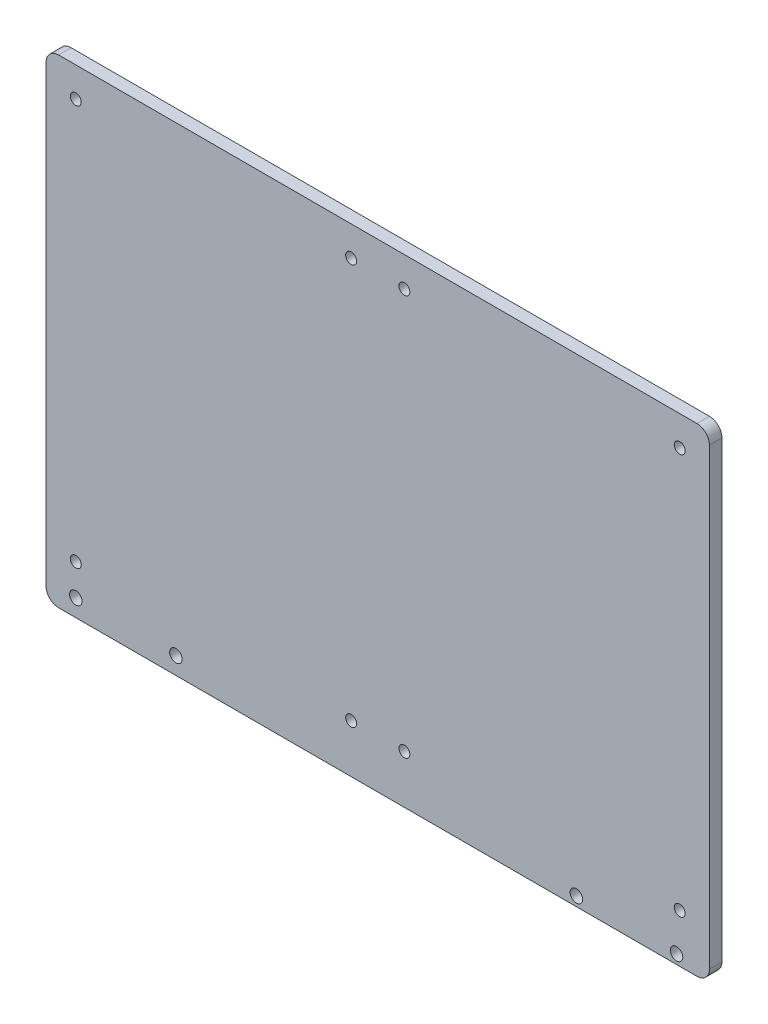
SolidWorks part; units mm, degrees
ref_plane "Front Plane" through (0, 0, 0) normal (0, 0, 1) x (1, 0, 0)
ref_plane "Top Plane" through (0, 0, 0) normal (0, 1, 0) x (1, 0, 0)
ref_plane "Right Plane" through (0, 0, 0) normal (1, 0, 0) x (0, 0, -1)
sketch "Sketch1" plane through (0, 0, 0) normal (0, 0, 1) x (1, 0, 0)
  line L1 (106, -76.5) -> (-106, -76.5)
  line L2 (106, -76.5) -> (106, 76.5)
  line L3 (106, 76.5) -> (-106, 76.5)
  line L4 (-106, -76.5) -> (-106, 76.5)
  line L5 (0, 76.5) -> (0, -76.5) construction
  line L6 (106, 0) -> (-106, 0) construction
  line L7 (-104, 74.5) -> (-1, 74.5) construction
  line L8 (-104, 74.5) -> (-104, -68.5) construction
  line L9 (-104, -68.5) -> (-1, -68.5) construction
  line L10 (-1, 74.5) -> (-1, -68.5) construction
  line L11 (-52.5, -68.5) -> (-52.5, 74.5) construction
  line L12 (-104, 3) -> (-1, 3) construction
  line L13 (1, 74.5) -> (104, 74.5) construction
  line L14 (1, 74.5) -> (1, -68.5) construction
  line L15 (1, -68.5) -> (104, -68.5) construction
  line L16 (104, 74.5) -> (104, -68.5) construction
  line L17 (52.5, -68.5) -> (52.5, 74.5) construction
  line L18 (1, 3) -> (104, 3) construction
  circle A0 centre (-96.5, -61) radius 1.75
  circle A1 centre (-8.5, -61) radius 1.75
  circle A2 centre (8.5, -61) radius 1.75
  circle A3 centre (96.5, -61) radius 1.75
  circle A4 centre (-96.5, 67) radius 1.75
  circle A5 centre (96.5, 67) radius 1.75
  circle A6 centre (8.5, 67) radius 1.75
  circle A7 centre (-8.5, 67) radius 1.75
  circle A8 centre (-96.5, -71) radius 2
  circle A9 centre (95.4803, -73.51) radius 2
  circle A10 centre (-64.5, -71) radius 2
  circle A11 centre (63.4803, -73.51) radius 2
  point P0 (0, 0)
  point P226 (-52.5, 3)
  point P227 (52.5, 3)
  dimension "D12" = 3.5
  dimension "D14" = 4
  dimension "D17" = 4
  dimension "D20" = 4
  dimension "D23" = 4
  dimension "D1" = 2
  dimension "D2" = 2
  dimension "D3" = 1
  dimension "D4" = 1
  dimension "D5" = 8
  dimension "D6" = 8
  dimension "D7" = 2
  dimension "D8" = 143
  dimension "D9" = 103
  dimension "D10" = 7.5
  dimension "D11" = 7.5
  dimension "D13" = 10
  dimension "D15" = 9.5
  dimension "D16" = 32
  dimension "D18" = 5.5
  dimension "D19" = 32
  dimension "D21" = 2.99
  dimension "D22" = 160
  dimension "D24" = 2.99
extrude "Boss-Extrude1" add sketch "Sketch1" along normal blind 4
fillet "Fillet1" radius 4 4 edges at (-106, -76.5, 2) (106, -76.5, 2) (-106, 76.5, 2) (106, 76.5, 2)
